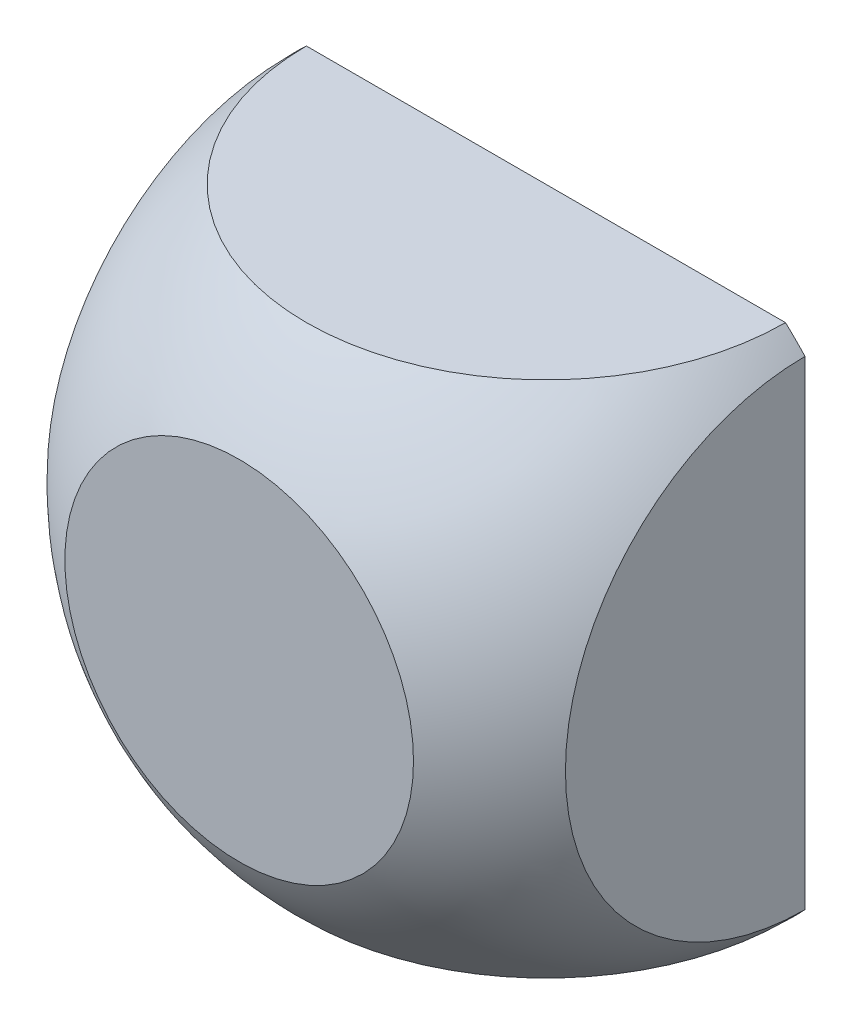
SolidWorks part; units mm, degrees
ref_plane "Plano frontal" through (0, 0, 0) normal (0, 0, 1) x (1, 0, 0)
ref_plane "Plano superior" through (0, 0, 0) normal (0, 1, 0) x (1, 0, 0)
ref_plane "Plano direito" through (0, 0, 0) normal (1, 0, 0) x (0, 0, -1)
sketch "Esboço4" plane through (0, 0, 0) normal (0, 0, 1) x (1, 0, 0)
  line L1 (-38, 38) -> (38, 38)
  line L2 (-38, 38) -> (-38, -38)
  line L3 (-38, -38) -> (38, -38)
  line L4 (38, 38) -> (38, -38)
  line L5 (-38, 38) -> (38, -38) construction
  line L6 (-38, -38) -> (38, 38) construction
  point P0 (0, 0)
extrude "Ressalto-extrusão2" add sketch "Esboço4" along normal blind 45
sketch "Esboço5" plane through (0, 0, 0) normal (1, 0, 0) x (0, 0, -1)
  line L0 (-104.6568, 0) -> (-51.7579, 0)
  line L1 (51.7579, 0) -> (104.6568, 0)
  arc A0 (51.7579, 0) -> (-51.7579, 0) centre (0, 0) ccw
  arc A1 (104.6568, 0) -> (-104.6568, 0) centre (0, 0) ccw
revolve "Corte-Revolução2" cut sketch "Esboço5" angle 360 about L0
